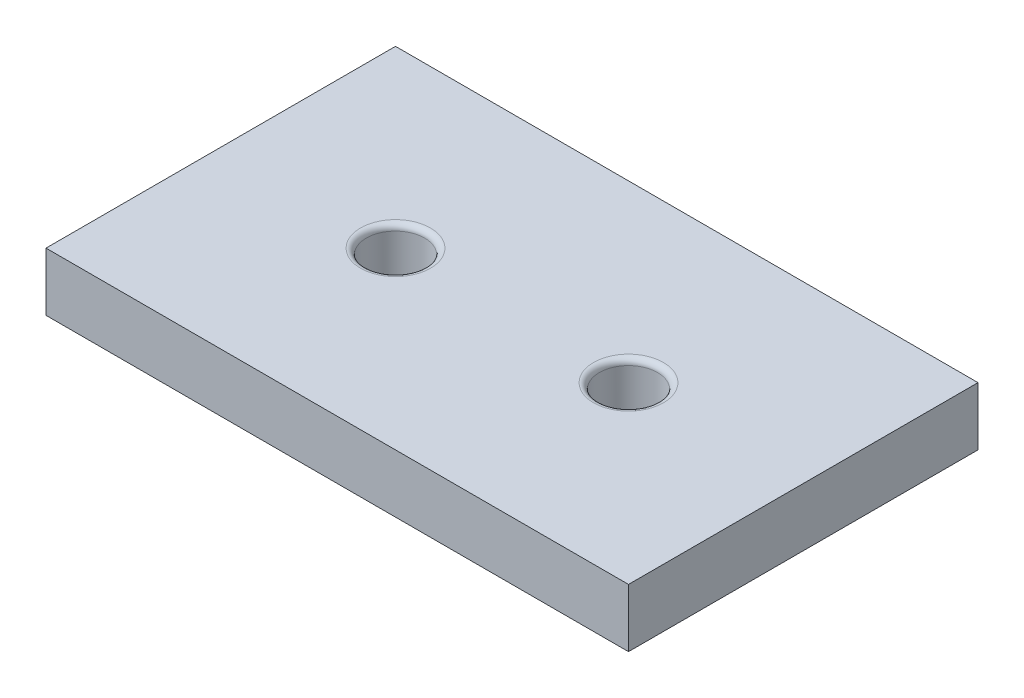
SolidWorks part; units mm, degrees
ref_plane "前视基准面" through (0, 0, 0) normal (0, 0, 1) x (1, 0, 0)
ref_plane "上视基准面" through (0, 0, 0) normal (0, 1, 0) x (1, 0, 0)
ref_plane "右视基准面" through (0, 0, 0) normal (1, 0, 0) x (0, 0, -1)
other "Configuration Table"
sketch "草图1" plane through (0, 0, 0) normal (0, 1, 0) x (1, 0, 0)
  line L1 (-50, -30) -> (50, -30)
  line L2 (-50, -30) -> (-50, 30)
  line L3 (-50, 30) -> (50, 30)
  line L4 (50, -30) -> (50, 30)
  line L5 (-50, -30) -> (50, 30) construction
  line L6 (-50, 30) -> (50, -30) construction
  point P0 (0, 0)
extrude "凸台-拉伸1" add sketch "草图1" along normal blind 10
sketch "草图2" plane through (0, 0, 0) normal (0, 1, 0) x (1, 0, 0)
  circle A0 centre (-20, 0) radius 5
extrude "切除-拉伸1" cut sketch "草图2" along normal blind 20
sketch "草图3" plane through (0, 0, 0) normal (0, 1, 0) x (1, 0, 0)
  circle A0 centre (20, 0) radius 5
extrude "切除-拉伸2" cut sketch "草图3" along normal blind 20
fillet "圆角1" radius 1 2 edges at (20, 10, -5) (-20, 10, -5)
sketch "草图4" plane through (0, 0, 0) normal (0, 1, 0) x (1, 0, 0)
  line L0 (-10, -20) -> (10, -20)
